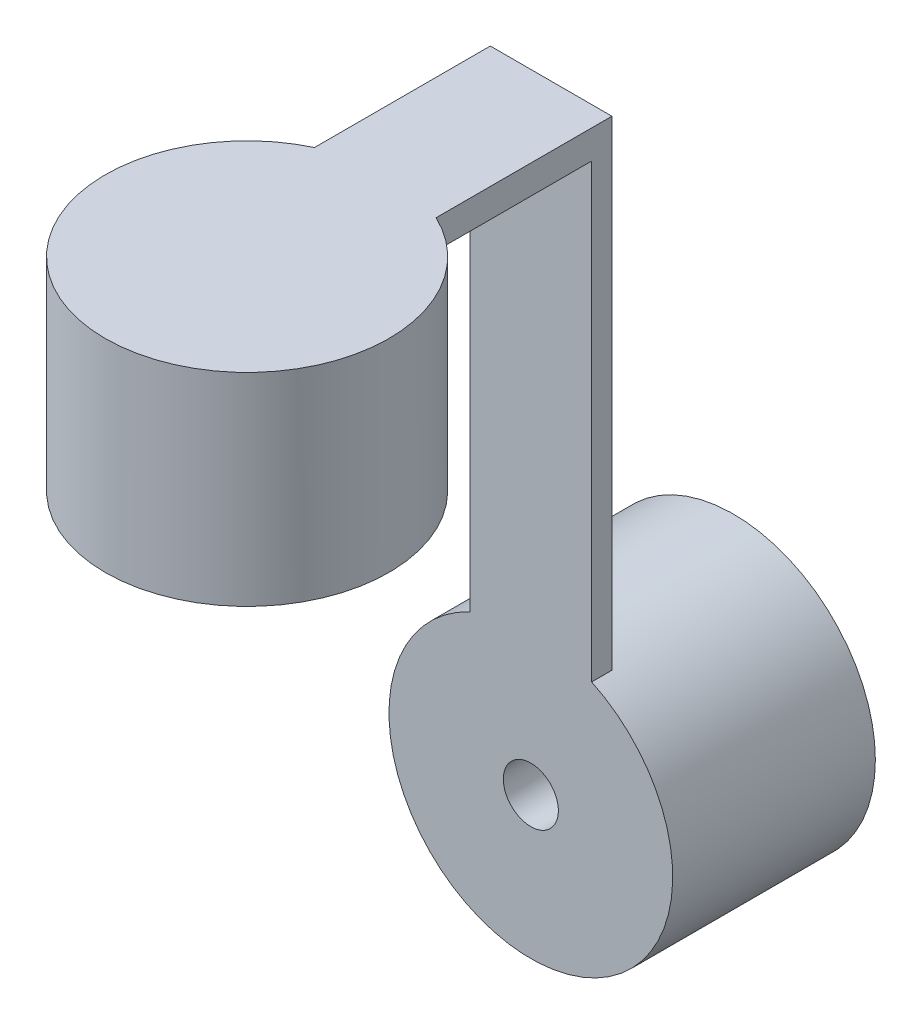
SolidWorks part; units mm, degrees
other "Markup1"
sketch "Sketch8" plane through (-35, -35, 0) normal (-0.9294, -0.3307, -0.1639) x (-0.285, 0.3609, 0.888)
ref_plane "Front Plane" through (0, 0, 0) normal (0, 0, 1) x (1, 0, 0)
ref_plane "Top Plane" through (0, 0, 0) normal (0, 1, 0) x (1, 0, 0)
ref_plane "Right Plane" through (0, 0, 0) normal (1, 0, 0) x (0, 0, -1)
sketch "Sketch1" plane through (0, 0, 0) normal (0, 0, 1) x (1, 0, 0)
  circle A0 centre (0, 0) radius 35
  dimension "D1" = 70
extrude "Boss-Extrude1" add sketch "Sketch1" along normal blind 50
sketch "Sketch2" plane through (0, 0, 0) normal (0, 1, 0) x (1, 0, 0)
  line L0 (-35, -50) -> (35, -50) construction
  line L1 (-15, -50) -> (15, -50)
  line L2 (-15, -50) -> (-15, -45)
  line L3 (-15, -45) -> (15, -45)
  line L4 (15, -50) -> (15, -45)
  line L5 (-35, 0) -> (-35, -50) construction
  dimension "D1" = 30
  dimension "D2" = 20
  dimension "D3" = 5
extrude "Boss-Extrude2" add sketch "Sketch2" along normal blind 150
sketch "Sketch3" plane through (0, 0, 50) normal (0, 0, 1) x (1, 0, 0)
  line L0 (15, 150) -> (15, 31.6228) construction
  line L1 (-15, 150) -> (15, 150)
  line L2 (-15, 150) -> (-15, 142.9209)
  line L3 (-15, 142.9209) -> (15, 142.9209)
  line L4 (15, 150) -> (15, 142.9209)
extrude "Boss-Extrude3" add sketch "Sketch3" along normal blind 70
sketch "Sketch5" plane through (0, 150, 0) normal (0, 1, 0) x (1, 0, 0)
  line L0 (15, -120) -> (-15, -120) construction
  circle A0 centre (0, -120) radius 35
  dimension "D1" = 70
extrude "Boss-Extrude4" add sketch "Sketch5" against normal blind 50
sketch "Sketch6" plane through (0, 0, 0) normal (0, 0, -1) x (-1, 0, 0)
  circle A0 centre (0, 0) radius 6.7913
extrude "Cut-Extrude1" cut sketch "Sketch6" against normal blind 50
sketch "Sketch7" plane through (0, 100, 0) normal (0, -1, 0) x (1, 0, 0)
  circle A0 centre (0, 120) radius 5
  dimension "D1" = 10
extrude "Cut-Extrude2" cut sketch "Sketch7" against normal blind 10
